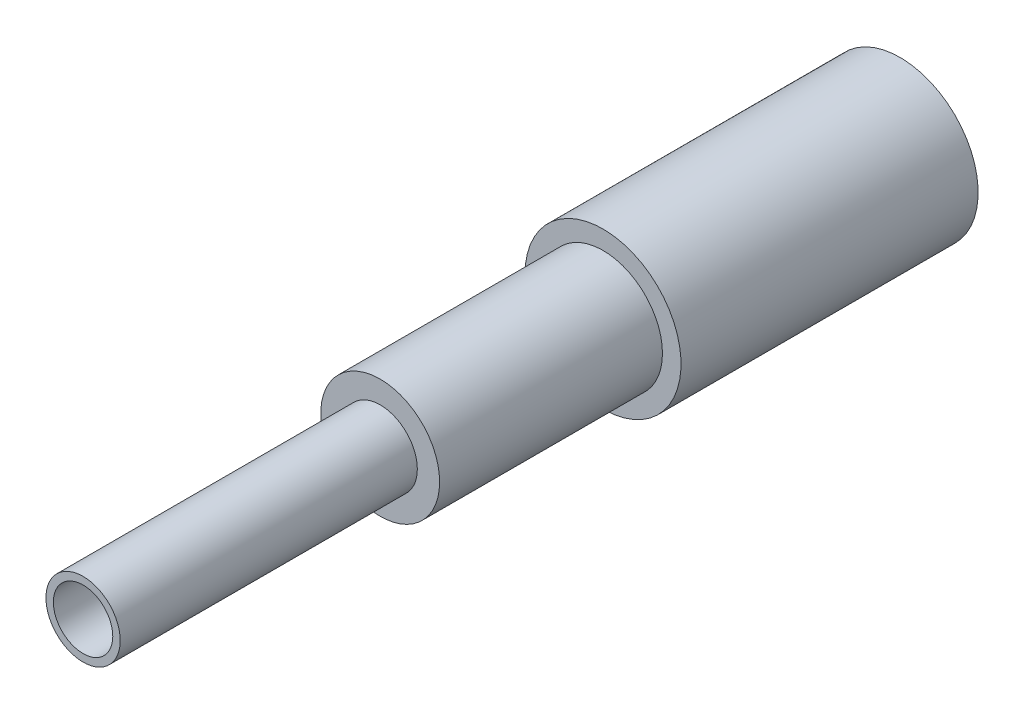
SolidWorks part; units mm, degrees
ref_plane "Front Plane" through (0, 0, 0) normal (0, 0, 1) x (1, 0, 0)
ref_plane "Top Plane" through (0, 0, 0) normal (0, 1, 0) x (1, 0, 0)
ref_plane "Right Plane" through (0, 0, 0) normal (1, 0, 0) x (0, 0, -1)
sketch "Sketch1" plane through (0, 0, 0) normal (0, 0, 1) x (1, 0, 0)
  circle A0 centre (0, 0) radius 8
  dimension "D1" = 16
extrude "Boss-Extrude2" add sketch "Sketch1" along normal blind 30
sketch "Sketch2" plane through (0, 0, 30) normal (0, 0, 1) x (1, 0, 0)
  circle A0 centre (0, 0) radius 5
  dimension "D1" = 10
extrude "Boss-Extrude3" add sketch "Sketch2" along normal blind 40
sketch "Sketch4" plane through (0, 0, 0) normal (0, 0, -1) x (-1, 0, 0)
  circle A0 centre (0, 0) radius 10.5
  dimension "D1" = 21
extrude "Boss-Extrude4" add sketch "Sketch4" along normal blind 40
shell "Shell1" thickness 1
sketch "Sketch5" plane through (0, 0, -40) normal (0, 0, -1) x (-1, 0, 0)
  circle A0 centre (0, 0) radius 9.5
  dimension "D1" = 19
extrude "Cut-Extrude2" cut sketch "Sketch5" against normal up to next
